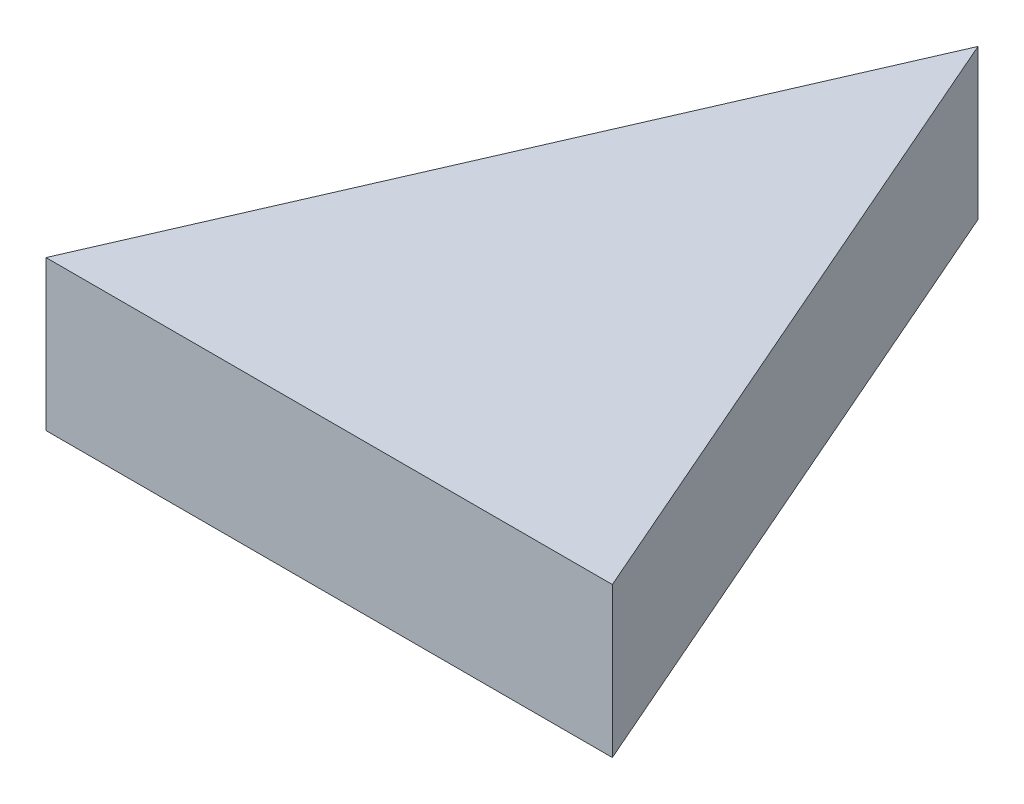
SolidWorks part; units mm, degrees
ref_plane "Front Plane" through (0, 0, 0) normal (0, 0, 1) x (1, 0, 0)
ref_plane "Top Plane" through (0, 0, 0) normal (0, 1, 0) x (1, 0, 0)
ref_plane "Right Plane" through (0, 0, 0) normal (1, 0, 0) x (0, 0, -1)
sketch "Sketch1" plane through (0, 0, 0) normal (0, 1, 0) x (1, 0, 0)
  line L0 (0, 0) -> (12, 0)
  line L1 (12, 0) -> (6, 13.7477)
  line L2 (6, 13.7477) -> (0, 0)
  dimension "D1" = 12
  dimension "D2" = 15
extrude "Boss-Extrude1" add sketch "Sketch1" along normal blind 3.175
